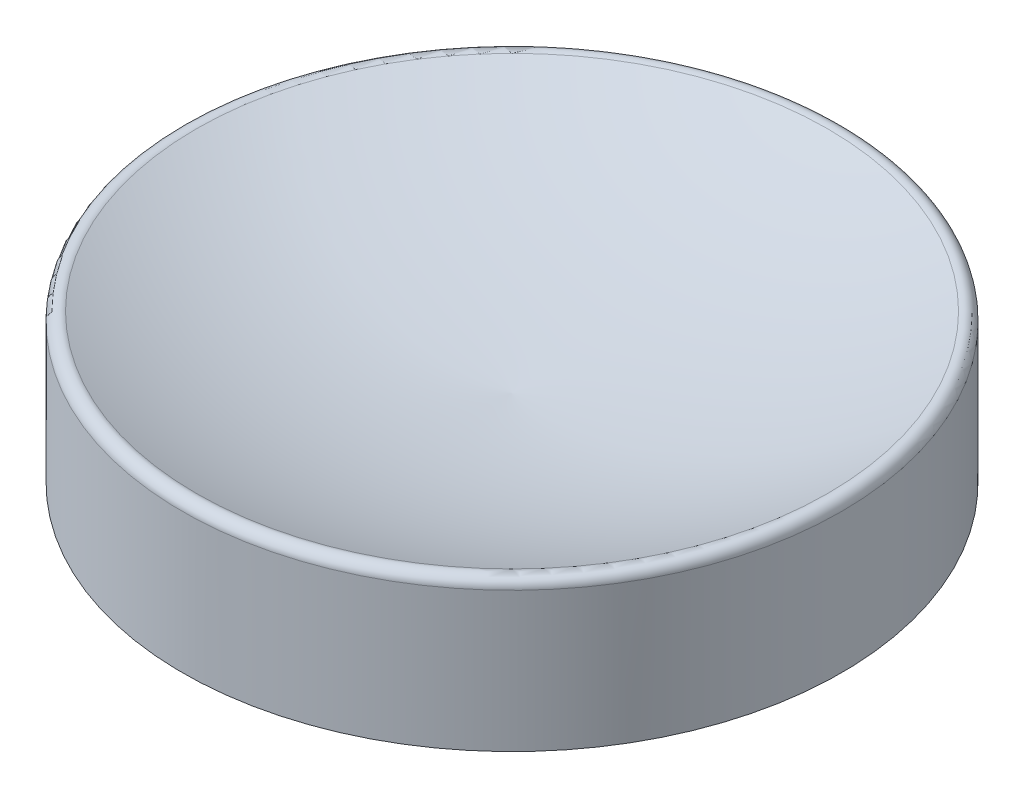
SolidWorks part; units mm, degrees
ref_plane "Front Plane" through (0, 0, 0) normal (0, 0, 1) x (1, 0, 0)
ref_plane "Top Plane" through (0, 0, 0) normal (0, 1, 0) x (1, 0, 0)
ref_plane "Right Plane" through (0, 0, 0) normal (1, 0, 0) x (0, 0, -1)
sketch "Sketch1" plane through (0, 0, 0) normal (0, 0, 1) x (1, 0, 0)
  line L0 (0, 2) -> (0, 0)
  line L1 (0, 0) -> (8.5, 0)
  line L2 (8.5, 0) -> (8.5, 4)
  spline S0 degree 3 poles (0, 2) (2.7479, 2.1693) (5.4761, 2.5111) (8.5, 4) knots 0 0 0 0 1 1 1 1
  dimension "D1" = 8.5
  dimension "D2" = 2
  dimension "D3" = 4
revolve "Revolve1" add sketch "Sketch1" angle 360 about L0
fillet "Fillet1" radius 0.25 1 edges at (-8.5, 4, 0)
sketch "Sketch2" plane through (0, 0, 0) normal (0, -1, 0) x (1, 0, 0)
  circle A0 centre (0, 0) radius 3
extrude "Boss-Extrude1" add sketch "Sketch2" along normal blind 2
